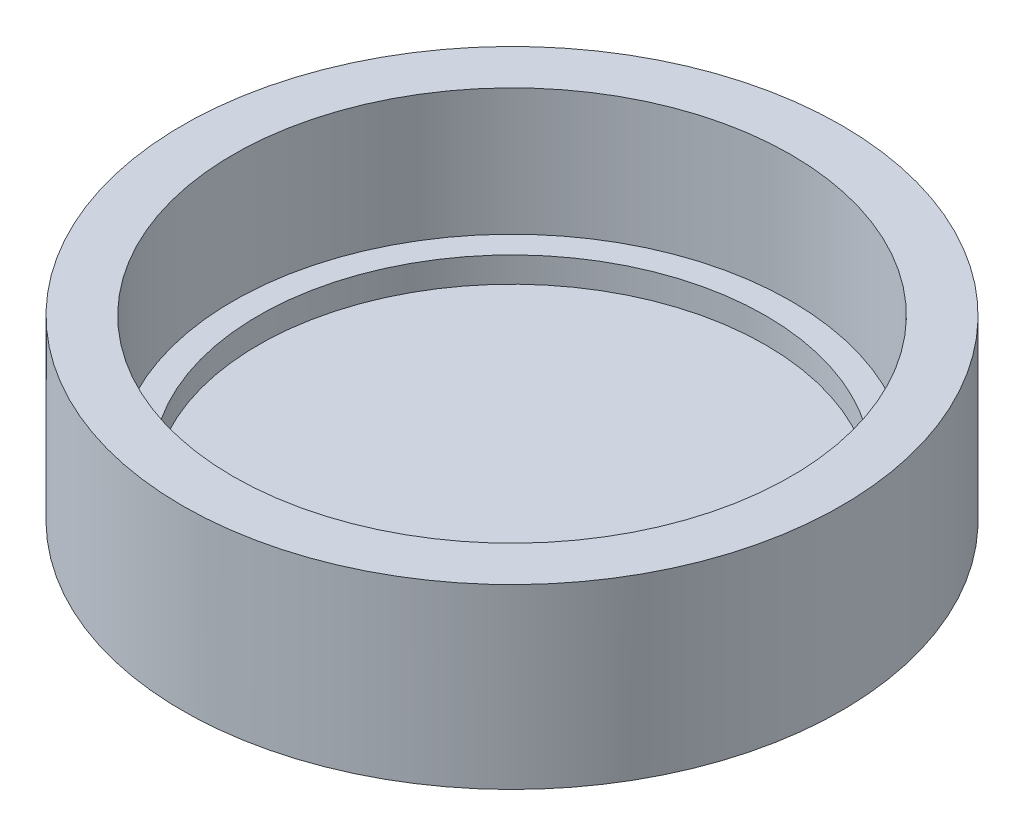
SolidWorks part; units mm, degrees
ref_plane "Plan de face" through (0, 0, 0) normal (0, 0, 1) x (1, 0, 0)
ref_plane "Plan de dessus" through (0, 0, 0) normal (0, 1, 0) x (1, 0, 0)
ref_plane "Plan de droite" through (0, 0, 0) normal (1, 0, 0) x (0, 0, -1)
sketch "Esquisse1" plane through (0, 0, 0) normal (0, 1, 0) x (1, 0, 0)
  circle A0 centre (0, 0) radius 11
  circle A1 centre (0, 0) radius 13
  dimension "D1" = 22
  dimension "D2" = 26
extrude "Boss.-Extru.1" add sketch "Esquisse1" along normal blind 6
sketch "Esquisse2" plane through (0, 0, 0) normal (0, -1, 0) x (1, 0, 0)
  circle A0 centre (0, 0) radius 13
extrude "Boss.-Extru.2" add sketch "Esquisse2" along normal blind 1
sketch "Esquisse3" plane through (0, 0, 0) normal (0, 1, 0) x (1, 0, 0)
  circle A0 centre (0, 0) radius 10
  circle A1 centre (0, 0) radius 11
  dimension "D1" = 20
extrude "Boss.-Extru.3" add sketch "Esquisse3" along normal blind 1
